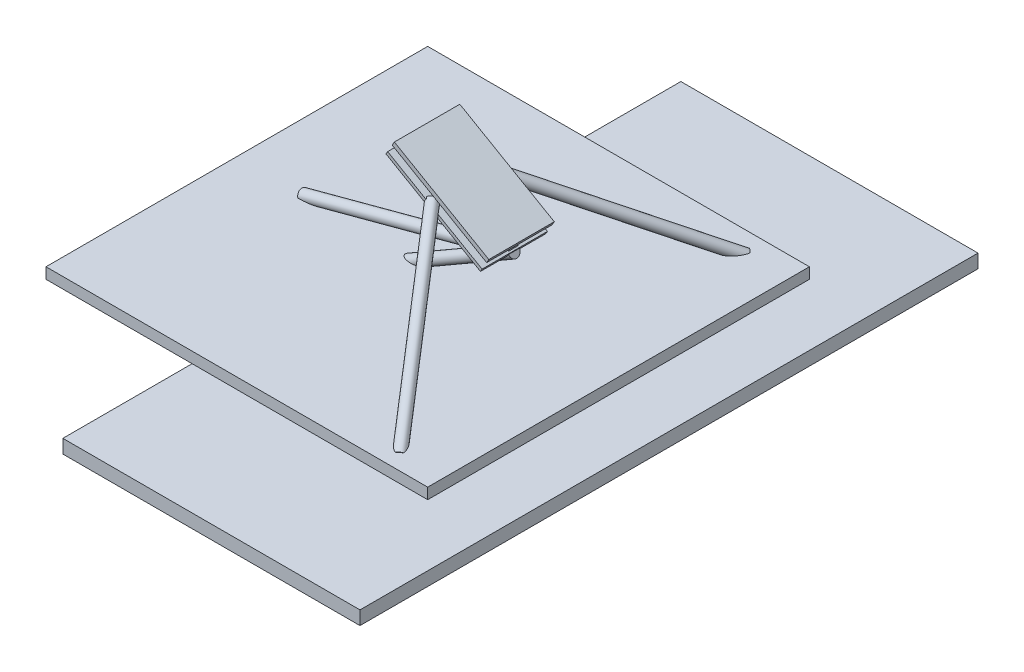
SolidWorks part; units mm, degrees
ref_plane "Piano frontale" through (0, 0, 0) normal (0, 0, 1) x (1, 0, 0)
ref_plane "Piano superiore" through (0, 0, 0) normal (0, 1, 0) x (1, 0, 0)
ref_plane "Piano destro" through (0, 0, 0) normal (1, 0, 0) x (0, 0, -1)
sketch "Schizzo1" plane through (0, 0, 0) normal (0, 0, 1) x (1, 0, 0)
  line L0 (-129.9038, 75) -> (43.3013, -25)
  line L1 (96.8471, 0) -> (-109.9815, 0) construction
  line L2 (0, 0) -> (88.9785, 154.1152) construction
  line L3 (-129.9038, 75) -> (214.3822, -123.7736) construction
  line L4 (43.3013, -25) -> (-343.0691, -128.5276)
  line L5 (-343.0691, -128.5276) -> (-340.4809, -138.1869)
  line L6 (-340.4809, -138.1869) -> (45.8895, -34.6593)
  line L7 (45.8895, -34.6593) -> (43.3013, -25)
  dimension "D1" = 200
  dimension "D2" = 50
  dimension "D3" = 30
  dimension "D4" = 400
  dimension "D5" = 15
  dimension "D6" = 135
  dimension "D7" = 10
ref_plane "Pedana" through (0, 0, 0) normal (0.5, 0.866, 0) x (0.866, -0.5, 0)
ref_plane "Piano2" through (0, 0, 0) normal (0, 0, 1) x (1, 0, 0)
sketch "Schizzo3" plane through (0, 0, 0) normal (0.5, 0.866, 0) x (0.866, -0.5, 0)
  line L0 (50, 0) -> (-232.8427, 0) construction
  line L1 (-150, -60) -> (50, -60)
  line L2 (-150, -60) -> (-150, 60)
  line L3 (-150, 60) -> (50, 60)
  line L4 (50, -60) -> (50, 60)
  line L5 (-150, -60) -> (50, 60) construction
  line L6 (-150, 60) -> (50, -60) construction
  point P0 (-50, 0)
  dimension "D1" = 120
extrude "Estrusione-Estrusione1" add sketch "Schizzo3" along normal mid plane 6
sketch "Schizzo4" plane through (0, 0, 0) normal (0, 0, 1) x (1, 0, 0)
  line L0 (-343.0691, -128.5276) -> (49.3736, -128.5276) construction
  line L1 (200096.8471, 0) -> (-200109.9815, 0) construction
  line L2 (0, 0) -> (0, -151.3249) construction
ref_plane "Base" through (0, -128.5276, 0) normal (0, -1, 0) x (-1, 0, 0)
sketch "Schizzo5" plane through (0, -128.5276, 0) normal (0, -1, 0) x (-1, 0, 0)
  line L0 (343.0691, 0) -> (-49.3736, 0) construction
  line L1 (-235.0688, 350) -> (464.9312, 350)
  line L2 (-235.0688, 350) -> (-235.0688, -350)
  line L3 (-235.0688, -350) -> (464.9312, -350)
  line L4 (464.9312, 350) -> (464.9312, -350)
  line L5 (-235.0688, 350) -> (464.9312, -350) construction
  line L6 (-235.0688, -350) -> (464.9312, 350) construction
  point P0 (114.9312, 0)
  dimension "D1" = 700
  dimension "D2" = 700
extrude "Estrusione-Estrusione2" add sketch "Schizzo5" along normal blind 20 separate body
sketch "Schizzo35" plane through (0, 0, 0) normal (0, 0, 1) x (1, 0, 0)
  line L0 (-90.7972, 60.442) -> (161.6221, -143.963) construction
  line L1 (95.2628, -55) -> (-95.2628, 55) construction
  line L3 (0, 0) -> (91.1789, 157.9265)
  line L4 (-128.4038, 77.5981) -> (44.8013, -22.4019) construction
  point P7 (-56.2917, 32.5)
  dimension "D1" = 81
  dimension "D2" = 65
sketch "Schizzo36" plane through (0, 0, 0) normal (0.5, 0.866, 0) x (0.866, -0.5, 0)
  line L0 (-65, 50) -> (-65, -50)
  dimension "D1" = 65
ref_plane "piano pistoni laterali" through (-6.3991, -7.9022, 0) normal (-0.6293, -0.7771, 0) x (0.7771, -0.6293, 0)
sketch "Schizzo6" plane through (-6.7778, -7.5955, 0) normal (0.6293, 0.7771, 0) x (-0.7771, 0.6293, 0)
  line L0 (125.6643, 0) -> (357.093, -231.4287) construction
  line L1 (-49.8718, 0) -> (185.2423, 0) construction
  line L2 (-0.4873, 0) -> (-0.4873, -375.2661) construction
  line L3 (125.6643, 0) -> (350.347, 224.6827) construction
  line L4 (127.3331, -50) -> (127.3331, 50) construction
  line L5 (127.3331, -50) -> (339.279, 161.9459) construction
  line L6 (127.3331, 50) -> (298.328, -120.9949) construction
  line L7 (200108.1127, 0) -> (-200216.6901, 0) construction
  point P7 (127.3331, 50)
  point P9 (127.3331, -50)
  point P10 (127.3331, 0)
  dimension "D1" = 45
  dimension "D2" = 45
  dimension "D3" = 100
ref_plane "Piano4" through (-90.1468, 0, 70.0572) normal (-0.7896, 0, 0.6136) x (-0.5495, 0.445, -0.7071)
sketch "Schizzo7" plane through (-100.6572, 68.4265, 121.2875) normal (0.6293, 0.7771, 0) x (-0.5495, 0.445, -0.7071)
  line L0 (148.3345, -73.8717) -> (60.0108, 156.5715) construction
  line L2 (55.0274, -45.7884) -> (434.0274, -45.7884)
  line L6 (55.0274, -45.7884) -> (296.8507, -45.7884) construction
  dimension "D1" = 379
sketch "Schizzo8" plane through (4.8742, -17.0311, -14.506) normal (-0.6293, -0.7771, 0) x (-0.5495, 0.445, -0.7071)
  line L6 (55.0274, -146.2526) -> (296.8507, -146.2526) construction
  line L7 (10.0407, -91.266) -> (-368.9593, -91.266)
  line L9 (10.0407, -101.266) -> (10.0407, -91.266)
  line L13 (10.0407, -101.266) -> (-368.9593, -101.266)
  line L15 (-368.9593, -101.266) -> (-368.9593, -91.266)
  dimension "D1" = 10
  dimension "D2" = 379
revolve "Rivoluzione5" add sketch "Schizzo8" angle 360 about L13
mirror "Specchia1" about plane through (0, 0, 0) normal (0, 0, 1) of "Rivoluzione5"
revolve "Rivoluzione1" add sketch "Schizzo1" angle 360 about L4
sketch "Misura distanza pistoni laterali" plane through (0, 0, 0) normal (0.5, 0.866, 0) x (0.866, -0.5, 0)
  line L0 (-127.8374, 50) -> (-127.8374, -50) construction
  line L1 (-127.8374, 50) -> (-127.8374, -50) construction
  dimension "D1" = 127.8374
  dimension "D2" = 100
sketch "Misura pistone centrale" plane through (0, 0, 0) normal (0, 0, 1) x (1, 0, 0)
  line L0 (43.3013, -25) -> (0, 0)
  dimension "D1" = 50
sketch "Schizzo16" plane through (0, 0, 0) normal (0.5, 0.866, 0) x (0.866, -0.5, 0)
  line L1 (165.3315, 19.5171) -> (531.3794, 53.828) construction
  line L3 (-127.8374, 50) -> (-337.1739, -161.9459) construction
  dimension "D1" = 40
sketch "Schizzo17" plane through (0, 0, 0) normal (0, 0, 1) x (1, 0, 0)
  line L0 (43.3013, -25) -> (-248.5493, -193.5)
  line L1 (-100000, -173205.0808) -> (100088.9785, 173359.196) construction
  line L2 (-248.5493, -193.5) -> (-243.5493, -202.1603)
  line L3 (-243.5493, -202.1603) -> (48.3013, -33.6603)
  line L4 (48.3013, -33.6603) -> (43.3013, -25)
  dimension "D1" = 337
  dimension "D2" = 150
  dimension "D3" = 193.5
  dimension "D4" = 434.6915
  dimension "D5" = 10
revolve "Rivoluzione4" add sketch "Schizzo17" angle 360 about L0
sketch "Schizzo18" plane through (0, 0, 0) normal (0, 0, 1) x (1, 0, 0)
  line L0 (43.3013, -25) -> (-232.9608, -184.5)
  line L2 (-232.9608, -184.5) -> (-227.9608, -193.1603)
  line L3 (-227.9608, -193.1603) -> (48.3013, -33.6603)
  line L4 (48.3013, -33.6603) -> (43.3013, -25)
  dimension "D1" = 319
  dimension "D5" = 10
sketch "Schizzo21" plane through (0, 0, 0) normal (0, 0, 1) x (1, 0, 0)
  line L0 (-232.9608, -184.5) -> (-232.9608, -204.5)
  dimension "D1" = 20
ref_plane "Piano5" through (0, -204.5, 0) normal (0, -1, 0) x (-1, 0, 0)
sketch "Schizzo22" plane through (0, -204.5, 0) normal (0, -1, 0) x (-1, 0, 0)
  line L0 (343.0691, 0) -> (-49.3736, 0) construction
  line L1 (-291.9572, 602.3105) -> (252.9608, 602.3105)
  line L2 (-291.9572, 602.3105) -> (-291.9572, -531.071)
  line L3 (-291.9572, -531.071) -> (252.9608, -531.071)
  line L4 (252.9608, 602.3105) -> (252.9608, -531.071)
  line L5 (172305.991, -18645.3511) -> (-172909.3603, 18718.6963) construction
  line L6 (105.7342, -50) -> (314.0043, 217.9935) construction
  point P0 (114.9312, 0)
  point P6 (232.9608, 0)
  point P10 (0, 0)
  point P14 (-291.9572, 35.6197)
  point P16 (-66.8719, -272.1025)
  point P17 (-164.1713, 412.2395)
  dimension "D1" = 20
  dimension "D6" = 397.1322
extrude "Estrusione-Estrusione3" add sketch "Schizzo22" along normal blind 25 separate body
sketch "Schizzo23" plane through (0, 0, 0) normal (0, 0, 1) x (1, 0, 0)
  line L0 (0, 0) -> (-12.5864, -15.5429)
  line L1 (-105.7342, 72.5378) -> (-238.6222, 180.1484) construction
  line L2 (0, 0) -> (12.5864, 15.5429)
  dimension "D1" = 20
  dimension "D2" = 20
ref_plane "Piano6" through (9.8769, 17.1073, 0) normal (0.5, 0.866, 0) x (0.866, -0.5, 0)
sketch "Schizzo24" plane through (9.8769, 17.1073, 0) normal (0.5, 0.866, 0) x (0.866, -0.5, 0)
  line L0 (50, -60) -> (50, 60) construction
  line L1 (-150, -60) -> (50, -60)
  line L2 (-150, -60) -> (-150, 60)
  line L3 (-150, 60) -> (50, 60)
  line L4 (50, -60) -> (50, 60)
  line L5 (50, 60) -> (-43.3406, 60) construction
extrude "Estrusione-Estrusione4" add sketch "Schizzo24" along normal blind 8 separate body
sketch "Schizzo28" plane through (0, 0, 0) normal (0, 0, 1) x (1, 0, 0)
  point P1 (-314.0043, 241.1915)
  dimension "D1" = 81.0434
sketch "Schizzo30" [suppressed] plane through (0, 0, 0) normal (0, 1, 0) x (1, 0, 0)
  line L0 (-110.9123, 50) -> (210.5954, 223.1145) construction
  line L1 (-110.9123, -50) -> (186.5593, -210.1723) construction
  line L2 (-18290.9782, 9738.9784) -> (18395.9021, -10014.9147) construction
  ellipse E0 centre (182.5694, 208.024) end of major axis (177.8285, 216.8287) minor radius 4.5315 construction
  point P0 (186.5593, 210.1723)
  point P1 (186.5593, -210.1723)
  point P10 (-232.9608, 0)
  dimension "D1" = 419.5201
  dimension "D2" = 420.3446
sketch "Schizzo31" plane through (0, 0, 0) normal (0, 0, 1) x (1, 0, 0)
  line L0 (-155519.9895, 125924.5202) -> (155590.8143, -126008.0412) construction
  line L1 (-142.1959, 102.0639) -> (129.3977, -117.8683) construction
  line L3 (-253.5493, -184.8397) -> (-243.5493, -202.1603) construction
  point P0 (164.9177, -147.1639)
  point P1 (-232.9608, -184.5)
  point P2 (-248.5493, -193.5)
  point P5 (132.7788, -120.6062)
  point P7 (-12.5864, -15.5429)
  point P8 (110.4976, -102.5633)
  point P15 (189.4503, -166.4979)
  point P16 (151.9784, -136.1538)
  dimension "D1" = 177.9571
  dimension "D2" = 400.5277
  dimension "D3" = 57.3462
  dimension "D4" = 20
sketch "Schizzo39" plane through (0, 0, 0) normal (0, 1, 0) x (1, 0, 0)
  point P0 (-232.9608, 0)
  point P1 (164.8617, 278.6273)
  point P2 (-56.2917, 50)
  point P3 (189.4503, 317.9935)
  point P5 (181.2728, 300.3118)
  point P6 (-105.7342, 50)
  point P8 (-105.7342, -50)
  point P10 (151.9784, -317.9935)
  point P12 (-248.5493, 0)
  point P18 (151.9784, 317.9935)
  dimension "D1" = 151.9784
  dimension "D2" = 400.5277
  dimension "D3" = 100
  dimension "D4" = 248.5493
  dimension "D5" = 635.9869
